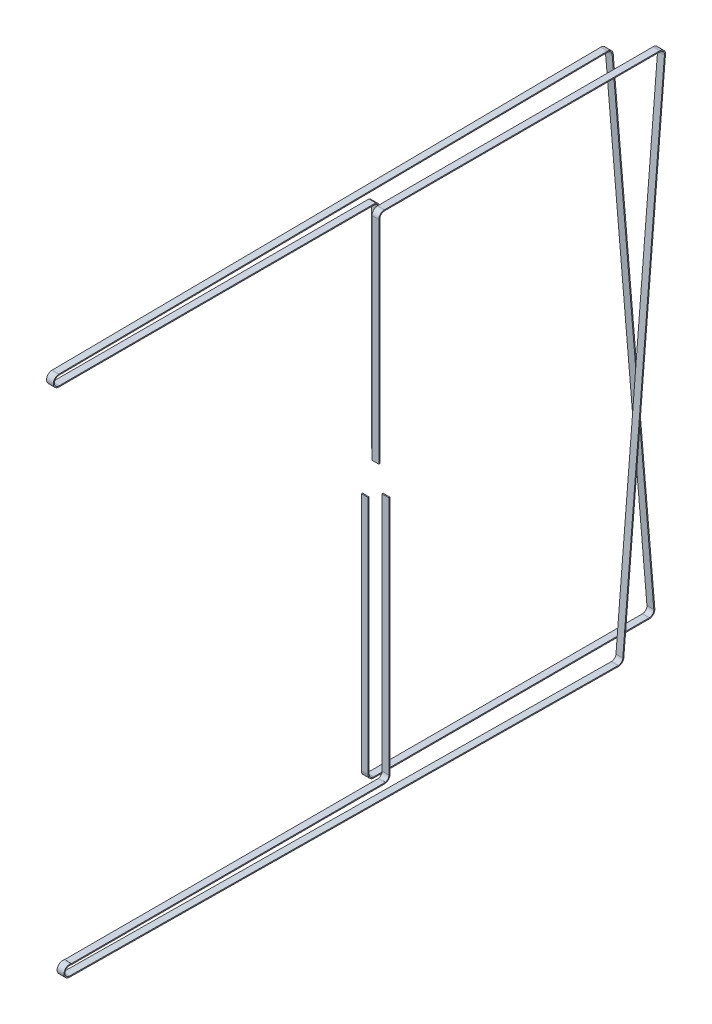
SolidWorks part; units mm, degrees
material "Полиуретан (11671)"
ref_plane "Спереди" through (0, 0, 0) normal (0, 0, 1) x (1, 0, 0)
ref_plane "Сверху" through (0, 0, 0) normal (0, 1, 0) x (1, 0, 0)
ref_plane "Справа" through (0, 0, 0) normal (1, 0, 0) x (0, 0, -1)
sketch "Эскиз1" plane through (43, 0, 0) normal (1, 0, 0) x (0, 0, -1)
  line L0 (-10, 24) -> (-372.611, 24)
  line L1 (-4.0206, 30.4965) -> (-58.822, 690.4965)
  line L2 (-365.211, 670) -> (-365.211, 391.0889)
  line L3 (-365.211, 391.0889) -> (-368.111, 391.0889) construction
  line L4 (-64.8604, 695.9997) -> (-787.059, 688.8997)
  line L5 (-787, 676.9) -> (-369.937, 676.9)
  line L6 (-378.611, 30) -> (-378.611, 346.0889)
  line L7 (-378.611, 346.0889) -> (-381.511, 346.0889) construction
  circle A0 centre (-10, 30) radius 6 construction
  arc A1 (-10, 24) -> (-4.0206, 30.4965) centre (-10, 30) ccw
  circle A2 centre (-372.611, 30) radius 6 construction
  circle A4 centre (-64.8015, 690) radius 6 construction
  arc A5 (-58.822, 690.4965) -> (-64.8604, 695.9997) centre (-64.8015, 690) ccw
  arc A6 (-787.059, 688.8997) -> (-787, 676.9) centre (-787, 682.9) ccw
  circle A7 centre (-787, 682.9) radius 2.675 construction
  arc A9 (-378.611, 30) -> (-372.611, 24) centre (-372.611, 30) ccw
  circle A10 centre (-372.611, 670) radius 7.4
  arc A11 (-365.211, 670) -> (-369.937, 676.9) centre (-372.611, 670) ccw
  dimension "D1" = 12
  dimension "D3" = 2815.1906
  dimension "D2" = 1.4
extrude "Вытянуть-Тонкостенный1" add sketch "Эскиз1" along normal blind 9 from offset 1 thin thin type one direction wall 1.4
sketch "Эскиз2" plane through (57, 0, 0) normal (1, 0, 0) x (0, 0, -1)
  line L0 (-371.3118, 22.7149) -> (-784.8851, 22.7149)
  line L1 (-365.211, 30) -> (-365.211, 346.0889)
  line L2 (-365.211, 346.0889) -> (-368.111, 346.0889) construction
  line L3 (-787.059, 11.1003) -> (-64.8604, 4.0003)
  line L4 (-58.822, 9.5035) -> (-4.0206, 669.5035)
  line L5 (-378.611, 670) -> (-378.611, 391.0889)
  line L6 (-378.611, 391.0889) -> (-381.511, 391.0889) construction
  line L8 (-10, 676) -> (-372.611, 676)
  arc A2 (-784.8851, 22.7149) -> (-787.059, 11.1003) centre (-787, 17.1) ccw
  circle A3 centre (-787, 17.1) radius 2.675 construction
  circle A5 centre (-372.611, 670) radius 6 construction
  circle A6 centre (-64.8015, 10) radius 6 construction
  arc A9 (-64.8604, 4.0003) -> (-58.822, 9.5035) centre (-64.8015, 10) ccw
  circle A10 centre (-10, 670) radius 6 construction
  arc A11 (-4.0206, 669.5035) -> (-10, 676) centre (-10, 670) ccw
  circle A12 centre (-372.611, 30) radius 7.4
  arc A13 (-371.3118, 22.7149) -> (-365.211, 30) centre (-372.611, 30) ccw
  arc A14 (-372.611, 676) -> (-378.611, 670) centre (-372.611, 670) ccw
  dimension "D1" = 12
  dimension "D3" = 2815.2921
  dimension "D2" = 1.4
extrude "Вытянуть-Тонкостенный2" add sketch "Эскиз2" along normal blind 9 from offset 1 separate body thin
